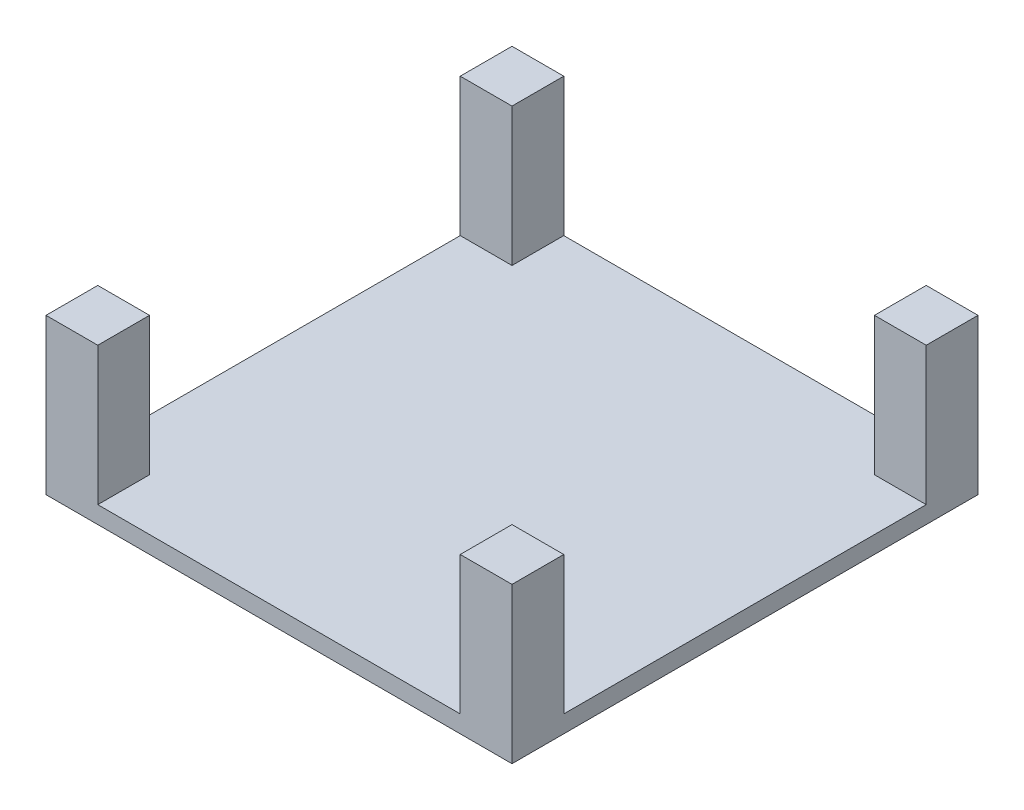
SolidWorks part; units mm, degrees
ref_plane "Front Plane" through (0, 0, 0) normal (0, 0, 1) x (1, 0, 0)
ref_plane "Top Plane" through (0, 0, 0) normal (0, 1, 0) x (1, 0, 0)
ref_plane "Right Plane" through (0, 0, 0) normal (1, 0, 0) x (0, 0, -1)
sketch "Sketch1" plane through (0, 0, 0) normal (0, 1, 0) x (1, 0, 0)
  line L1 (0, 0) -> (135, 0)
  line L2 (0, 0) -> (0, 135)
  line L3 (0, 135) -> (135, 135)
  line L4 (135, 0) -> (135, 135)
  dimension "D1" = 135
  dimension "D2" = 135
extrude "Boss-Extrude1" add sketch "Sketch1" along normal blind 5
sketch "Sketch2" plane through (0, 5, 0) normal (0, 1, 0) x (1, 0, 0)
  line L0 (67.5, 135) -> (67.5, 0) construction
  line L1 (0, 0) -> (15, 0)
  line L2 (0, 0) -> (0, 15)
  line L3 (0, 15) -> (15, 15)
  line L4 (15, 0) -> (15, 15)
  line L5 (135, 135) -> (0, 135) construction
  line L6 (0, 0) -> (135, 0) construction
  line L7 (0, 67.5) -> (135, 67.5) construction
  line L8 (0, 135) -> (0, 0) construction
  line L9 (135, 0) -> (135, 135) construction
  line L10 (135, 15) -> (120, 15)
  line L11 (120, 0) -> (120, 15)
  line L12 (135, 0) -> (120, 0)
  line L13 (135, 0) -> (135, 15)
  line L14 (135, 135) -> (135, 120)
  line L15 (135, 135) -> (120, 135)
  line L16 (120, 135) -> (120, 120)
  line L17 (135, 120) -> (120, 120)
  line L18 (0, 120) -> (15, 120)
  line L19 (15, 135) -> (15, 120)
  line L20 (0, 135) -> (15, 135)
  line L21 (0, 135) -> (0, 120)
  dimension "D1" = 15
  dimension "D2" = 15
extrude "Boss-Extrude2" add sketch "Sketch2" along normal blind 40
